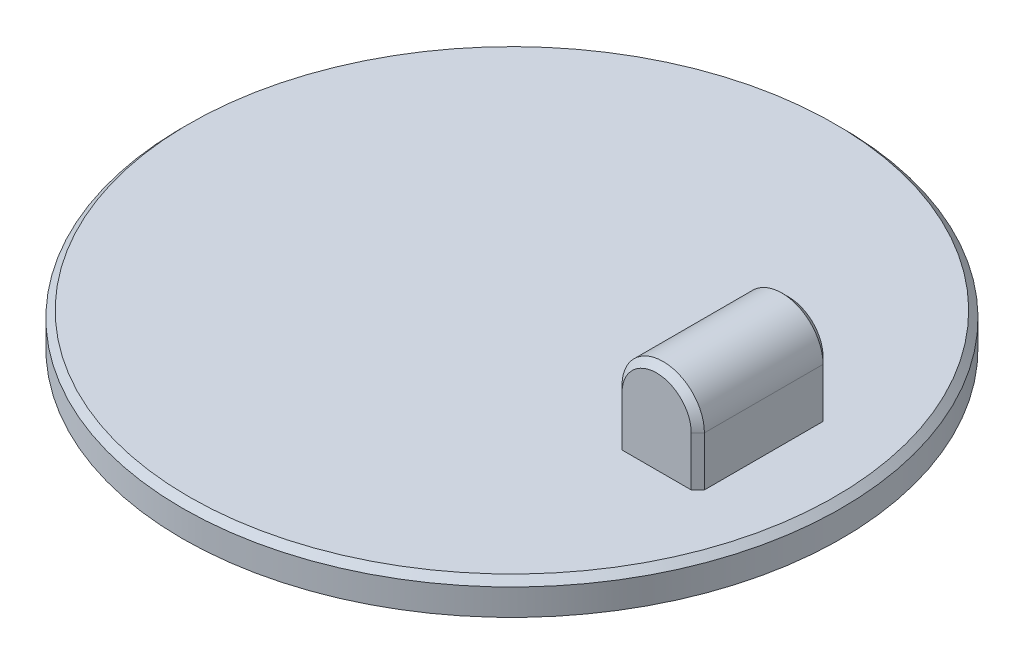
SolidWorks part; units mm, degrees
ref_plane "前视基准面" through (0, 0, 0) normal (0, 0, 1) x (1, 0, 0)
ref_plane "上视基准面" through (0, 0, 0) normal (0, 1, 0) x (1, 0, 0)
ref_plane "右视基准面" through (0, 0, 0) normal (1, 0, 0) x (0, 0, -1)
sketch "草图1" plane through (0, 0, 0) normal (0, 1, 0) x (1, 0, 0)
  circle A0 centre (0, 0) radius 100
  dimension "D1" = 200
extrude "凸台-拉伸1" add sketch "草图1" along normal blind 10
sketch "草图2" plane through (0, 0, 0) normal (0, 0, 1) x (1, 0, 0)
  line L0 (100, 10) -> (-100, 10) construction
  line L2 (51.399, 25) -> (51.399, 10)
  line L3 (51.399, 10) -> (76.399, 10)
  line L4 (76.399, 25) -> (76.399, 10)
  arc A0 (76.399, 25) -> (51.399, 25) centre (63.899, 25) ccw
  point P5 (0, 0)
  point P8 (61.399, 23.306)
  dimension "D1" = 25
  dimension "D2" = 15
extrude "凸台-拉伸2" add sketch "草图2" along normal mid plane 40
chamfer "倒角1" distance 2 angle 45 6 edges at (76.399, 17.5, -20) (51.399, 17.5, -20) (63.899, 37.5, -20) (76.399, 17.5, 20) (51.399, 17.5, 20) (63.899, 37.5, 20)
chamfer "倒角2" distance 2 angle 45 1 edges at (0, 10, 100)
